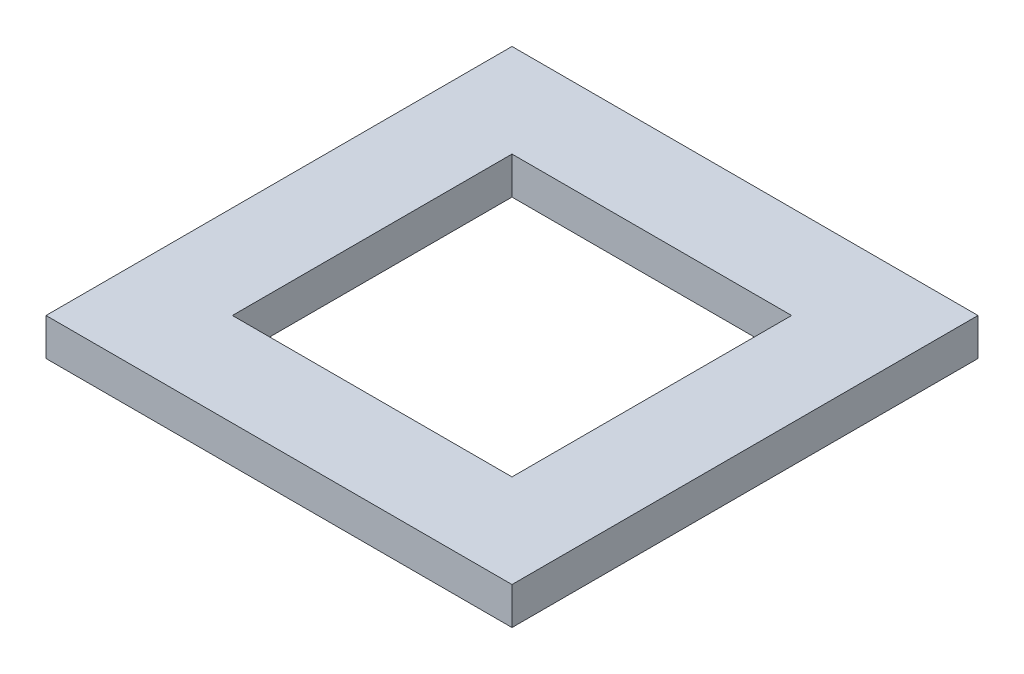
SolidWorks part; units mm, degrees
ref_plane "Front Plane" through (0, 0, 0) normal (0, 0, 1) x (1, 0, 0)
ref_plane "Top Plane" through (0, 0, 0) normal (0, 1, 0) x (1, 0, 0)
ref_plane "Right Plane" through (0, 0, 0) normal (1, 0, 0) x (0, 0, -1)
sketch "Sketch1" plane through (0, 0, 0) normal (0, 1, 0) x (1, 0, 0)
  line L0 (-7.5, -7.5) -> (-7.5, 7.5)
  line L1 (-7.5, -7.5) -> (7.5, -7.5)
  line L2 (-7.5, 7.5) -> (7.5, 7.5)
  line L3 (7.5, -7.5) -> (7.5, 7.5)
  line L4 (-7.5, -7.5) -> (7.5, 7.5) construction
  line L5 (-7.5, 7.5) -> (7.5, -7.5) construction
  line L6 (-12.5, -12.5) -> (-12.5, 12.5)
  line L7 (-12.5, 12.5) -> (12.5, 12.5)
  line L8 (12.5, -12.5) -> (12.5, 12.5)
  line L9 (-12.5, -12.5) -> (12.5, -12.5)
  point P1 (0, 0)
  dimension "D1" = 15
  dimension "D2" = 15
  dimension "D3" = 5
extrude "Boss-Extrude1" add sketch "Sketch1" along normal blind 2
